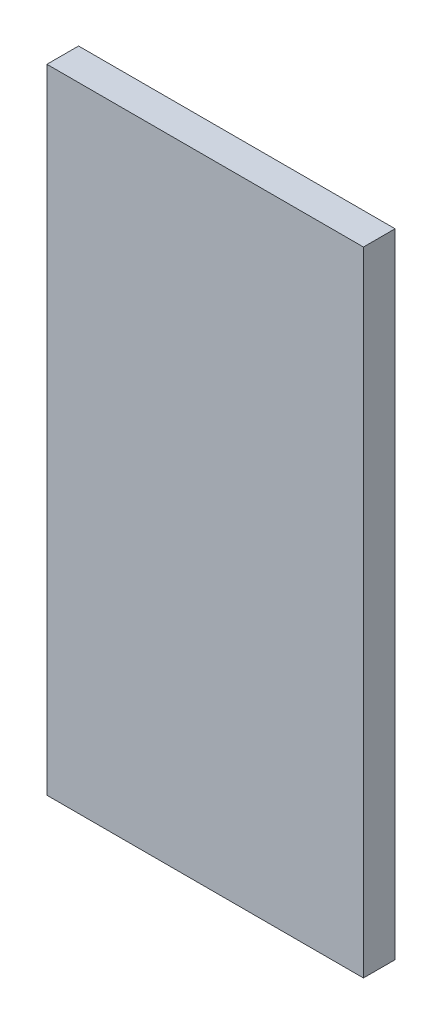
SolidWorks part; units mm, degrees
ref_plane "Front Plane" through (0, 0, 0) normal (0, 0, 1) x (1, 0, 0)
ref_plane "Top Plane" through (0, 0, 0) normal (0, 1, 0) x (1, 0, 0)
ref_plane "Right Plane" through (0, 0, 0) normal (1, 0, 0) x (0, 0, -1)
sketch "Sketch1" plane through (0, 0, 0) normal (0, 0, 1) x (1, 0, 0)
  line L1 (0, 0) -> (10, 0)
  line L2 (0, 0) -> (0, 20)
  line L3 (0, 20) -> (10, 20)
  line L4 (10, 0) -> (10, 20)
extrude "Boss-Extrude1" add sketch "Sketch1" along normal blind 1
